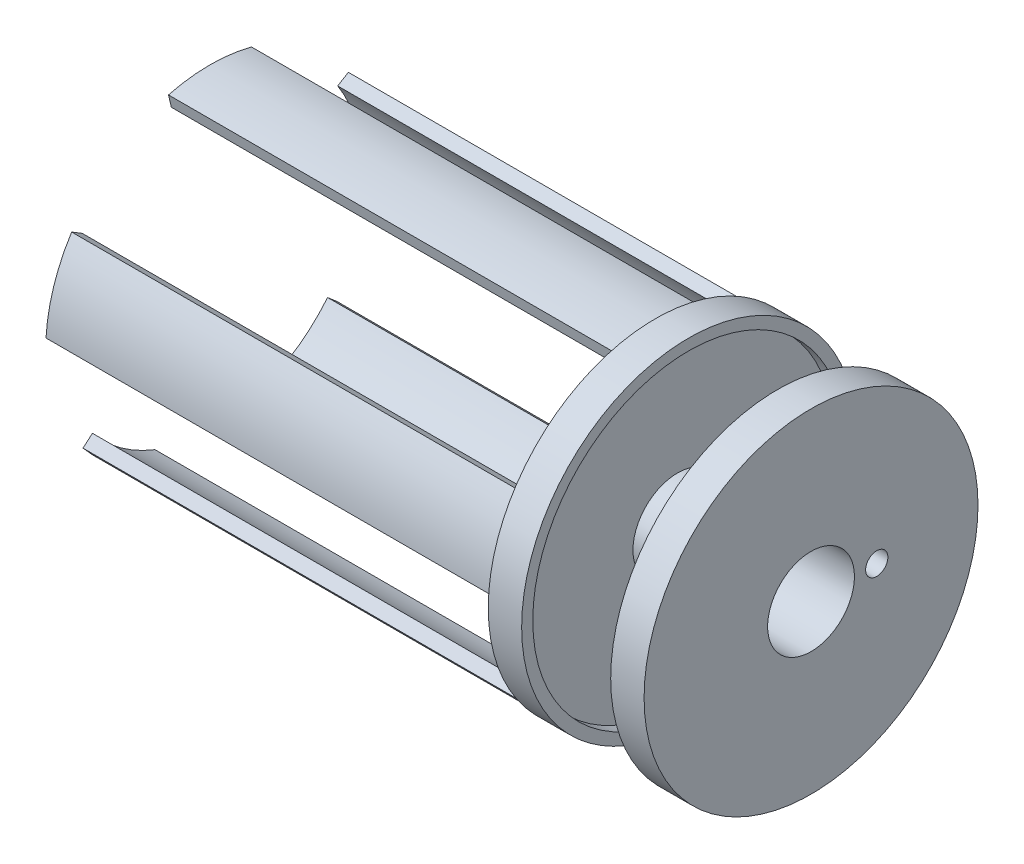
SolidWorks part; units mm, degrees
ref_plane "Front" through (0, 0, 0) normal (0, 0, 1) x (1, 0, 0)
ref_plane "Top" through (0, 0, 0) normal (0, 1, 0) x (1, 0, 0)
ref_plane "Right" through (0, 0, 0) normal (1, 0, 0) x (0, 0, -1)
sketch "Sketch1" plane through (0, 0, 0) normal (0, 0, 1) x (1, 0, 0)
  line L0 (-52.1154, 0) -> (17.8846, 0)
  line L1 (-52.1154, 0) -> (-52.1154, 75)
  line L2 (-52.1154, 75) -> (-37.1154, 75)
  line L3 (-37.1154, 75) -> (-37.1154, 70)
  line L4 (-37.1154, 70) -> (-42.1154, 70)
  line L5 (-42.1154, 70) -> (-42.1154, 20)
  line L6 (-42.1154, 20) -> (7.8846, 20)
  line L7 (7.8846, 20) -> (7.8846, 70)
  line L8 (7.8846, 70) -> (2.8846, 70)
  line L9 (2.8846, 70) -> (2.8846, 75)
  line L10 (2.8846, 75) -> (17.8846, 75)
  line L11 (17.8846, 75) -> (17.8846, 0)
  line L12 (-114.1966, 0) -> (101.9563, 0) construction
  dimension "D1" = 70
  dimension "D2" = 75
  dimension "D3" = 10
  dimension "D4" = 5
  dimension "D5" = 50
  dimension "D6" = 20
  dimension "D8" = 5
  dimension "D9" = 75
  dimension "D10" = 70
  dimension "D11" = 15
revolve "Revolve2" add sketch "Sketch1" angle 360 about L12
sketch "Sketch2" plane through (-52.1154, 0, 0) normal (-1, 0, 0) x (0, 0, 1)
  line L0 (-18.6502, 71.4045) -> (-17.3672, 65.9517)
  line L1 (18.6502, 71.4045) -> (17.3672, 65.9517)
  arc A2 (18.6502, 71.4045) -> (-18.6502, 71.4045) centre (0, 0) ccw
  arc A3 (17.3672, 65.9517) -> (-17.3672, 65.9517) centre (0, 0) ccw
sketch "Sketch4" plane through (17.8846, 0, 0) normal (1, 0, 0) x (0, 0, -1)
  circle A0 centre (29.5197, 0) radius 5
extrude "Cut-Extrude4" cut sketch "Sketch4" against normal blind 16 contours A0
extrude "Boss-Extrude1" add sketch "Sketch2" along normal blind 200 contours A3 L0 A2 L1
pattern_circular "CirPattern1" count 5 over 360 about axis through (0, 0, 0) along (1, 0, 0) of "Boss-Extrude1"
sketch "Sketch6" plane through (17.8846, 0, 0) normal (1, 0, 0) x (0, 0, -1)
  circle A0 centre (0, 0) radius 19.5
extrude "Cut-Extrude5" cut sketch "Sketch6" against normal through all
